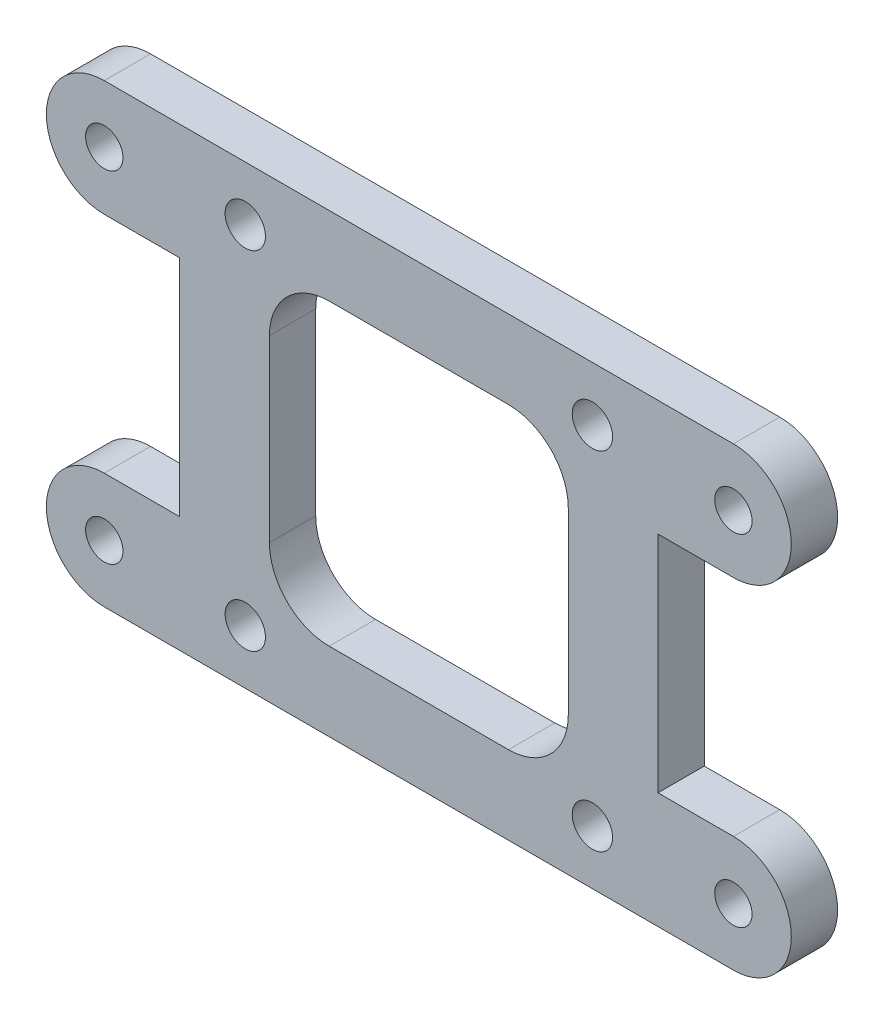
SolidWorks part; units mm, degrees
ref_plane "Front Plane" through (0, 0, 0) normal (0, 0, 1) x (1, 0, 0)
ref_plane "Top Plane" through (0, 0, 0) normal (0, 1, 0) x (1, 0, 0)
ref_plane "Right Plane" through (0, 0, 0) normal (1, 0, 0) x (0, 0, -1)
sketch "Sketch1" plane through (0, 0, 0) normal (0, 0, 1) x (1, 0, 0)
  line L0 (-14.806, -13.5975) -> (8.4224, 9.631) construction
  line L1 (-13.1918, -11.9833) -> (-19.1918, -11.9833) construction
  line L2 (-22.2918, 13.2667) -> (-22.2918, 5.5618) construction
  line L3 (-24.2418, 13.2667) -> (-19.1918, 13.2667)
  line L4 (-19.1918, 5.5167) -> (-24.2418, 5.5167)
  line L5 (-3.1918, 13.2667) -> (-3.1918, -17.2333) construction
  line L6 (-19.1918, 13.2667) -> (12.8082, 13.2667)
  line L7 (-13.9418, -1.9833) -> (-27.8182, -1.9833) construction
  line L8 (-19.1918, -17.2333) -> (12.8082, -17.2333)
  line L9 (-22.2918, -17.2333) -> (-22.2918, -9.5284) construction
  line L10 (-19.1918, -9.4833) -> (-24.2418, -9.4833)
  line L11 (-19.1918, 5.5167) -> (-19.1918, -9.4833)
  line L12 (-24.2418, -17.2333) -> (-19.1918, -17.2333)
  line L13 (12.8082, 5.5167) -> (12.8082, -9.4833)
  line L14 (15.9082, -17.2333) -> (15.9082, -9.5284) construction
  line L15 (6.8082, 8.0167) -> (-13.1918, -11.9833) construction
  line L16 (-13.1918, 4.0167) -> (-13.1918, -7.9833)
  line L17 (-9.1918, -11.9833) -> (2.8082, -11.9833)
  line L18 (-9.1918, 8.0167) -> (2.8082, 8.0167)
  line L19 (6.8082, 4.0167) -> (6.8082, -7.9833)
  line L20 (6.8082, -11.9833) -> (12.8082, -11.9833) construction
  line L21 (-13.1918, 8.0167) -> (6.8082, -11.9833) construction
  line L22 (-13.9418, -1.9833) -> (6.0582, -1.9833) construction
  line L23 (15.9082, 13.2667) -> (15.9082, 5.5618) construction
  line L24 (17.8582, -17.2333) -> (12.8082, -17.2333)
  line L25 (12.8082, -9.4833) -> (17.8582, -9.4833)
  line L26 (12.8082, 5.5167) -> (17.8582, 5.5167)
  line L27 (17.8582, 13.2667) -> (12.8082, 13.2667)
  circle A0 centre (-14.806, 9.631) radius 1.35
  circle A1 centre (8.4224, -13.5975) radius 1.35
  circle A2 centre (-14.806, -13.5975) radius 1.35
  circle A3 centre (8.4224, 9.631) radius 1.35
  arc A4 (-9.1918, 8.0167) -> (-13.1918, 4.0167) centre (-9.1918, 4.0167) ccw
  arc A5 (2.8082, 8.0167) -> (6.8082, 4.0167) centre (2.8082, 4.0167) cw
  arc A6 (2.8082, -11.9833) -> (6.8082, -7.9833) centre (2.8082, -7.9833) ccw
  arc A7 (-9.1918, -11.9833) -> (-13.1918, -7.9833) centre (-9.1918, -7.9833) cw
  circle A8 centre (-24.2418, 9.4143) radius 1.25
  arc A9 (-24.2418, -17.2333) -> (-24.2418, -9.4833) centre (-24.2418, -13.3583) cw
  circle A10 centre (-24.2418, -13.3808) radius 1.25
  arc A11 (17.8582, 13.2667) -> (17.8582, 5.5167) centre (17.8582, 9.3917) cw
  arc A12 (-24.2418, 13.2667) -> (-24.2418, 5.5167) centre (-24.2418, 9.3917) ccw
  circle A13 centre (17.8582, -13.3808) radius 1.25
  arc A14 (17.8582, -17.2333) -> (17.8582, -9.4833) centre (17.8582, -13.3583) ccw
  circle A15 centre (17.8582, 9.4143) radius 1.25
  point P41 (-10.4418, 8.0167)
  point P47 (4.0582, 8.0167)
  point P50 (6.0582, 6.0167)
  point P53 (4.0582, -11.9833)
  point P56 (6.0582, -9.9833)
  point P59 (-10.4418, -11.9833)
  point P62 (-13.9418, -9.9833)
  dimension "D8" = 2.7
  dimension "D3" = 4
  dimension "D4" = 2.7
  dimension "D7" = 2.7
  dimension "D11" = 2.7
  dimension "D2" = 32
  dimension "D5" = 20
  dimension "D10" = 30.5
extrude "Extrude1" add sketch "Sketch1" along normal blind 3.1
